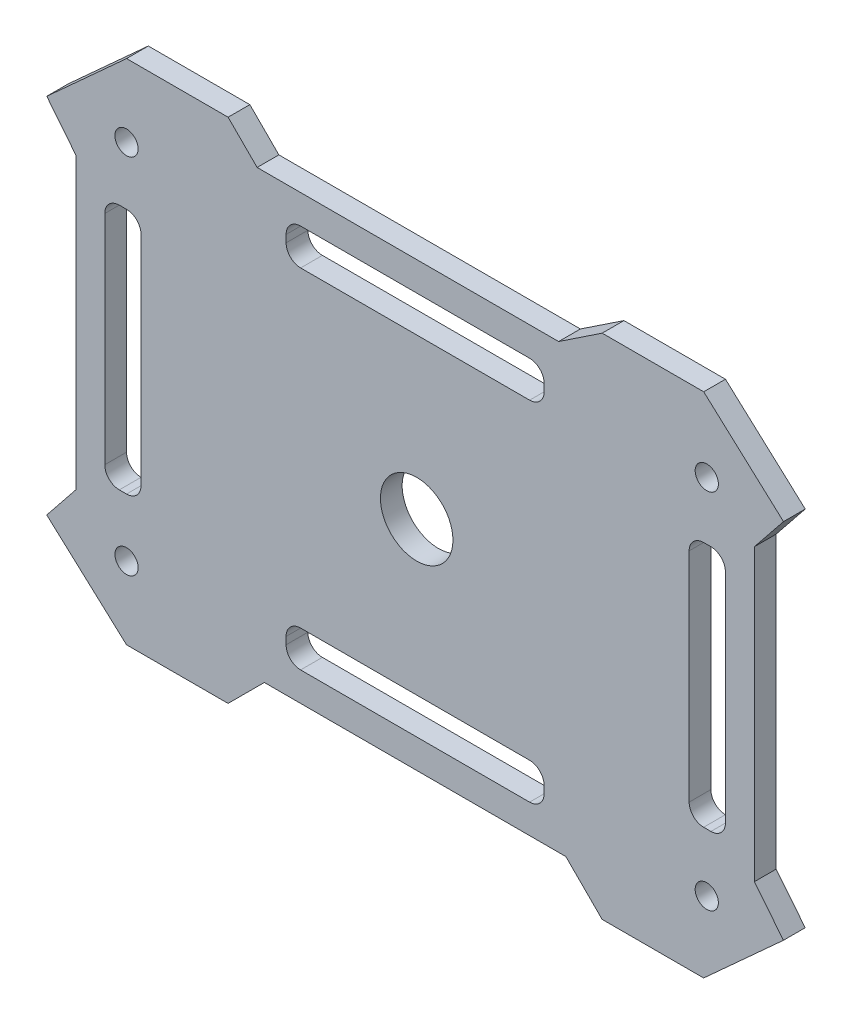
SolidWorks part; units mm, degrees
ref_plane "Front Plane" through (0, 0, 0) normal (0, 0, 1) x (1, 0, 0)
ref_plane "Top Plane" through (0, 0, 0) normal (0, 1, 0) x (1, 0, 0)
ref_plane "Right Plane" through (0, 0, 0) normal (1, 0, 0) x (0, 0, -1)
sketch "Sketch1" plane through (0, 0, 0) normal (0, 0, 1) x (1, 0, 0)
  line L0 (-45.5433, 37.859) -> (-34.5433, 47.859)
  line L1 (-16.5433, 43.859) -> (25.0311, 43.859)
  line L2 (52.0224, 32.859) -> (52.0224, -7.141)
  line L3 (-45.5476, -12.141) -> (-41.5476, -7.141)
  line L4 (-20.5433, 47.859) -> (-16.5433, 43.859)
  line L5 (-34.5433, 47.859) -> (-20.5433, 47.859)
  line L6 (45.0307, 47.859) -> (56.0307, 37.859)
  line L7 (-45.5476, -12.141) -> (-34.5476, -22.141)
  line L8 (-34.5476, -22.141) -> (-20.5476, -22.141)
  line L9 (45.0224, -22.141) -> (56.0224, -12.141)
  line L10 (31.0224, -22.141) -> (45.0224, -22.141)
  line L11 (31.0307, 47.859) -> (45.0307, 47.859)
  line L12 (-41.5476, 32.859) -> (-45.5433, 37.859)
  line L13 (-41.5476, -7.141) -> (-41.5476, 32.859)
  line L14 (26.022, -17.141) -> (-15.5476, -17.141)
  line L15 (52.0224, 32.859) -> (56.0307, 37.859)
  line L16 (52.0224, -7.141) -> (56.0224, -12.141)
  line L17 (25.0311, 43.859) -> (31.0307, 47.859)
  line L18 (-15.5476, -17.141) -> (-20.5476, -22.141)
  line L19 (26.022, -17.141) -> (31.0224, -22.141)
  line L20 (-35.5476, 29.859) -> (-34.5476, 29.859)
  line L21 (-37.5476, 27.859) -> (-37.5476, -2.141)
  line L22 (-35.5476, -4.141) -> (-34.5476, -4.141)
  line L23 (-32.5476, 27.859) -> (-32.5476, -2.141)
  line L24 (-10.5433, 39.859) -> (21.0307, 39.859)
  line L25 (-12.5433, 37.859) -> (-12.5433, 36.859)
  line L26 (-10.5433, 34.859) -> (21.0307, 34.859)
  line L27 (23.0307, 37.859) -> (23.0307, 36.859)
  line L28 (46.0224, 29.859) -> (45.0224, 29.859)
  line L29 (48.0224, 27.859) -> (48.0224, -2.141)
  line L30 (46.0224, -4.141) -> (45.0224, -4.141)
  line L31 (43.0224, 27.859) -> (43.0224, -2.141)
  line L32 (21.0224, -13.141) -> (-10.5476, -13.141)
  line L33 (23.0224, -11.141) -> (23.0224, -10.141)
  line L34 (21.0224, -8.141) -> (-10.5476, -8.141)
  line L35 (-12.5476, -11.141) -> (-12.5476, -10.141)
  arc A0 (46.0224, -4.141) -> (48.0224, -2.141) centre (46.0224, -2.141) ccw
  arc A1 (43.0224, -2.141) -> (45.0224, -4.141) centre (45.0224, -2.141) ccw
  arc A2 (48.0224, 27.859) -> (46.0224, 29.859) centre (46.0224, 27.859) ccw
  arc A3 (45.0224, 29.859) -> (43.0224, 27.859) centre (45.0224, 27.859) ccw
  arc A4 (21.0307, 34.859) -> (23.0307, 36.859) centre (21.0307, 36.859) ccw
  arc A5 (23.0307, 37.859) -> (21.0307, 39.859) centre (21.0307, 37.859) ccw
  arc A6 (-12.5433, 36.859) -> (-10.5433, 34.859) centre (-10.5433, 36.859) ccw
  arc A7 (-10.5433, 39.859) -> (-12.5433, 37.859) centre (-10.5433, 37.859) ccw
  arc A8 (-32.5476, 27.859) -> (-34.5476, 29.859) centre (-34.5476, 27.859) ccw
  arc A9 (-35.5476, 29.859) -> (-37.5476, 27.859) centre (-35.5476, 27.859) ccw
  arc A10 (-34.5476, -4.141) -> (-32.5476, -2.141) centre (-34.5476, -2.141) ccw
  arc A11 (-37.5476, -2.141) -> (-35.5476, -4.141) centre (-35.5476, -2.141) ccw
  circle A12 centre (5.4567, 12.859) radius 5
  arc A13 (21.0224, -13.141) -> (23.0224, -11.141) centre (21.0224, -11.141) ccw
  arc A14 (23.0224, -10.141) -> (21.0224, -8.141) centre (21.0224, -10.141) ccw
  arc A15 (-10.5476, -8.141) -> (-12.5476, -10.141) centre (-10.5476, -10.141) ccw
  arc A16 (-12.5476, -11.141) -> (-10.5476, -13.141) centre (-10.5476, -11.141) ccw
  circle A17 centre (-34.5476, 37.859) radius 1.6
  circle A18 centre (45.4524, 37.859) radius 1.6
  circle A19 centre (45.4524, -12.141) radius 1.6
  circle A20 centre (-34.5476, -12.141) radius 1.6
extrude "Boss-Extrude1" add sketch "Sketch1" along normal blind 3
